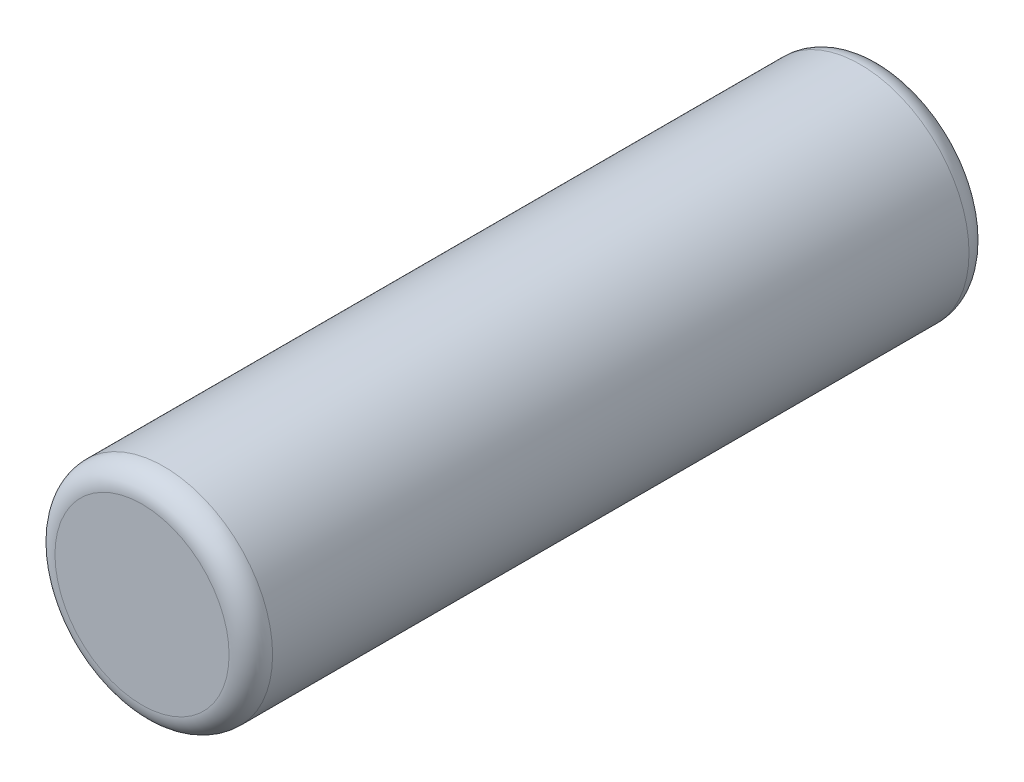
SolidWorks part; units mm, degrees
ref_plane "Plano frontal" through (0, 0, 0) normal (0, 0, 1) x (1, 0, 0)
ref_plane "Plano superior" through (0, 0, 0) normal (0, 1, 0) x (1, 0, 0)
ref_plane "Plano direito" through (0, 0, 0) normal (1, 0, 0) x (0, 0, -1)
sketch "Esboço2" plane through (0, 0, 0) normal (0, 0, 1) x (1, 0, 0)
  circle A0 centre (0, 0) radius 10
  dimension "D1" = 20
extrude "Ressalto-extrusão1" add sketch "Esboço2" along normal mid plane 68
fillet "Filete1" radius 2 2 edges at (10, 0, -34) (10, 0, 34)
